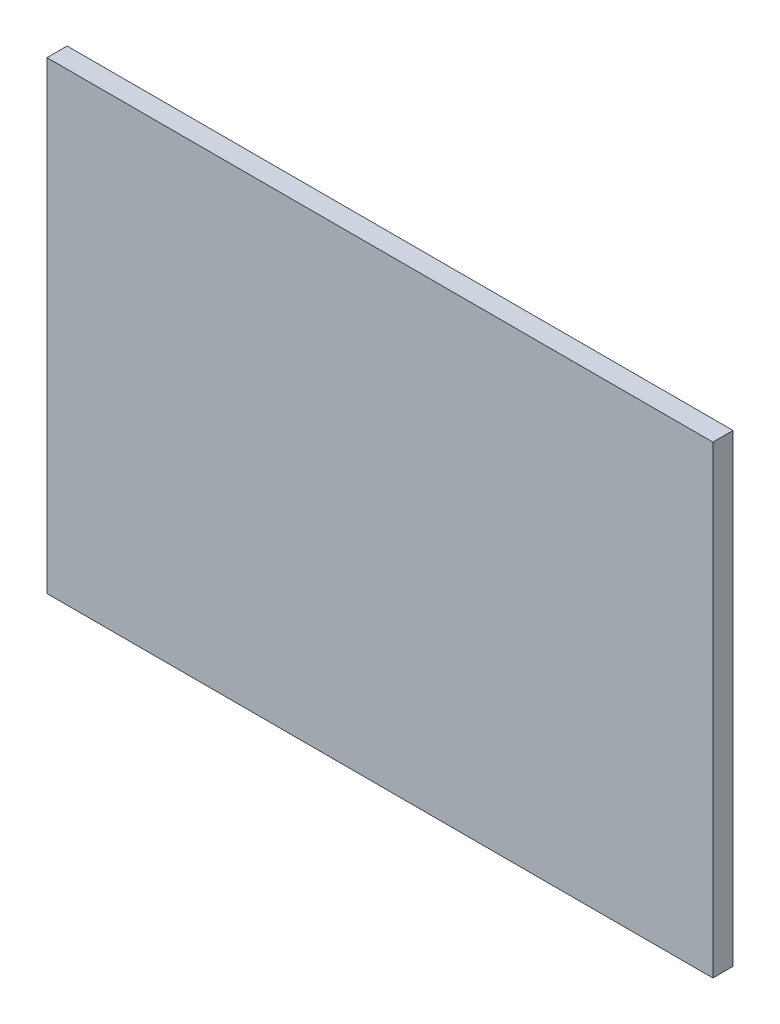
SolidWorks part; units mm, degrees
ref_plane "Alzado" through (0, 0, 0) normal (0, 0, 1) x (1, 0, 0)
ref_plane "Planta" through (0, 0, 0) normal (0, 1, 0) x (1, 0, 0)
ref_plane "Vista lateral" through (0, 0, 0) normal (1, 0, 0) x (0, 0, -1)
sketch "Croquis1" plane through (0, 0, 0) normal (0, 0, 1) x (1, 0, 0)
  line L1 (-330, -230) -> (330, -230)
  line L2 (-330, -230) -> (-330, 230)
  line L3 (-330, 230) -> (330, 230)
  line L4 (330, -230) -> (330, 230)
  line L5 (-330, -230) -> (330, 230) construction
  line L6 (-330, 230) -> (330, -230) construction
  point P0 (0, 0)
  dimension "D1" = 660
  dimension "D2" = 460
extrude "Saliente-Extruir1" add sketch "Croquis1" along normal blind 20
